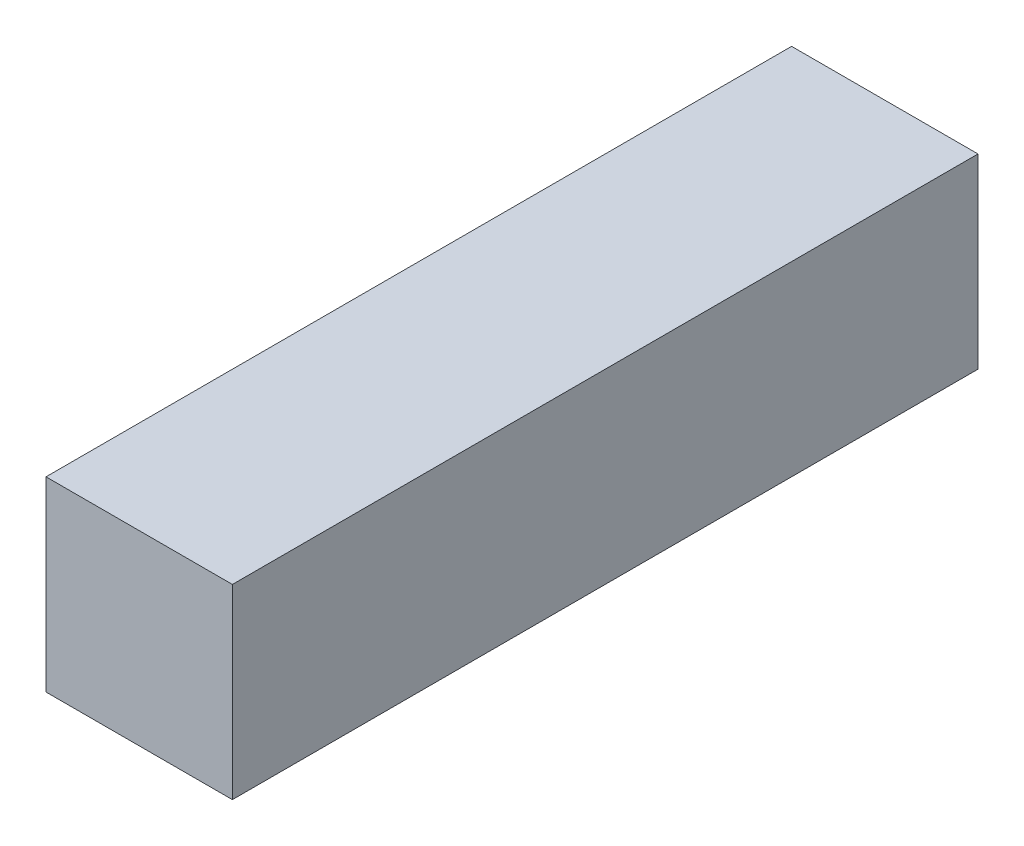
SolidWorks part; units mm, degrees
material "ﾁｰｸ材"
ref_plane "正面" through (0, 0, 0) normal (0, 0, 1) x (1, 0, 0)
ref_plane "平面" through (0, 0, 0) normal (0, 1, 0) x (1, 0, 0)
ref_plane "右側面" through (0, 0, 0) normal (1, 0, 0) x (0, 0, -1)
sketch "ｽｹｯﾁ1" plane through (0, 0, 0) normal (0, 0, 1) x (1, 0, 0)
  line L1 (2.75, 2.75) -> (-2.75, 2.75)
  line L2 (2.75, 2.75) -> (2.75, -2.75)
  line L3 (2.75, -2.75) -> (-2.75, -2.75)
  line L4 (-2.75, 2.75) -> (-2.75, -2.75)
  line L5 (2.75, 2.75) -> (-2.75, -2.75) construction
  line L6 (2.75, -2.75) -> (-2.75, 2.75) construction
  point P0 (0, 0)
  dimension "D1" = 5.5
  dimension "D2" = 5.5
extrude "ﾎﾞｽ - 押し出し1" add sketch "ｽｹｯﾁ1" along normal blind 22
